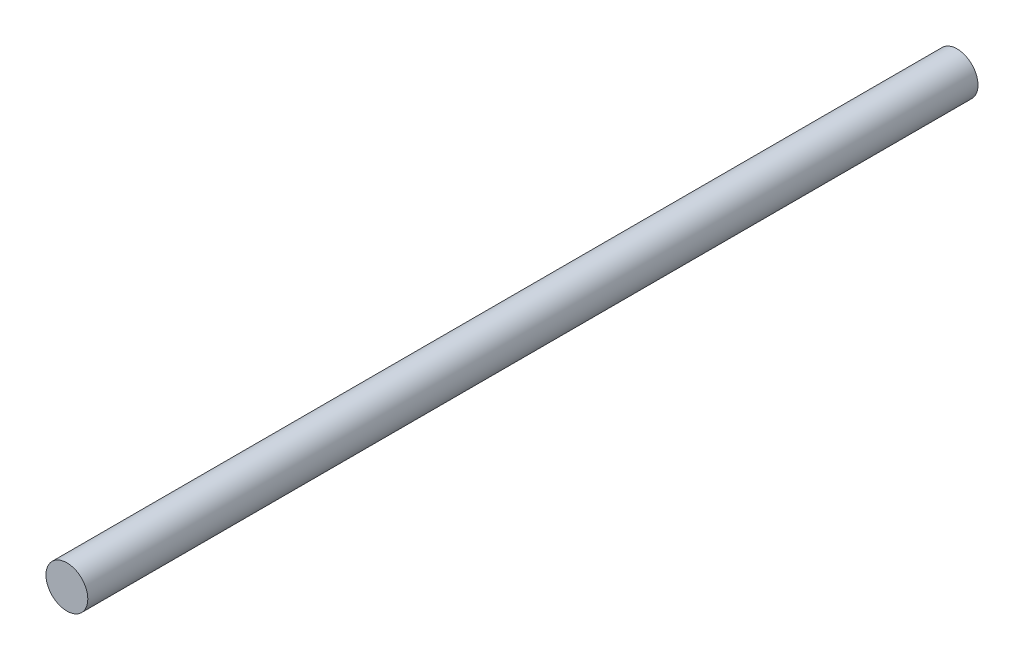
SolidWorks part; units mm, degrees
ref_plane "Front Plane" through (0, 0, 0) normal (0, 0, 1) x (1, 0, 0)
ref_plane "Top Plane" through (0, 0, 0) normal (0, 1, 0) x (1, 0, 0)
ref_plane "Right Plane" through (0, 0, 0) normal (1, 0, 0) x (0, 0, -1)
sketch "Sketch2" plane through (0, 0, 0) normal (0, 0, 1) x (1, 0, 0)
  circle A0 centre (0, 0) radius 1.04
extrude "Boss-Extrude1" add sketch "Sketch2" along normal blind 44.2396
